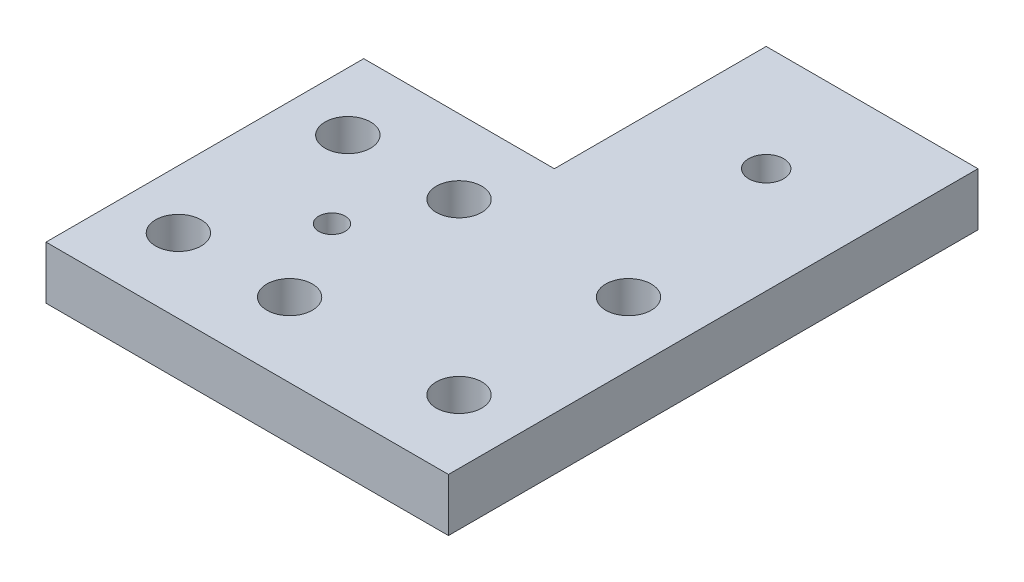
SolidWorks part; units mm, degrees
ref_plane "Ebene vorne" through (0, 0, 0) normal (0, 0, 1) x (1, 0, 0)
ref_plane "Ebene oben" through (0, 0, 0) normal (0, 1, 0) x (1, 0, 0)
ref_plane "Ebene rechts" through (0, 0, 0) normal (1, 0, 0) x (0, 0, -1)
sketch "Skizze1" plane through (0, 0, 0) normal (0, 1, 0) x (1, 0, 0)
  line L0 (-9, 15) -> (-9, -15)
  line L1 (-9, -15) -> (29, -15)
  line L2 (9, 35) -> (9, 15)
  line L3 (-9, 15) -> (9, 15)
  line L4 (29, -15) -> (29, 35)
  line L7 (9, 35) -> (29, 35)
  point P3 (0, 15)
  point P5 (-9, 0)
  dimension "D3" = 20
  dimension "D1" = 38
  dimension "D2" = 30
  dimension "D4" = 50
extrude "Aufsatz-Linear austragen1" add sketch "Skizze1" along normal blind 5 contours L0 L1 L4 L7 L2 L3
hole_wizard "Durchgangsloch für M41" positions "Skizze2" profile "Skizze3" hole size "M4" standard "DIN" end condition up to next
sketch "Skizze2" plane through (0, 5, 0) normal (0, 1, 0) x (1, 0, 0)
  line L1 (29, -15) -> (29, 35) construction
  line L2 (0, 0) -> (29, 0) construction
  line L3 (29, -15) -> (29, 35) construction
  point P0 (7, 8)
  point P2 (23, 8)
  point P4 (7, -8)
  point P6 (23, -8)
  dimension "D1" = 16
  dimension "D2" = 16
  dimension "D3" = 6
sketch "Skizze3" plane through (7, 5, -8) normal (1, 0, 0) x (0, 0, 1)
  line L0 (0, 0) -> (0, 5)
  line L1 (0, 5) -> (2.15, 5)
  line L2 (2.15, 5) -> (2.15, 0)
  line L5 (2.15, 0) -> (0, 0)
  line L11 (0, -6.35) -> (0, 107.95) construction
  dimension "Bohrerdurchmesser" = 4.3
  dimension "Bohrungstiefe" = 5
hole_wizard "Durchgangsloch für M42" positions "Skizze4" profile "Skizze5" hole size "M4" standard "DIN" end condition up to next
sketch "Skizze4" plane through (0, 5, 0) normal (0, 1, 0) x (1, 0, 0)
  line L2 (-9, 15) -> (-9, -15) construction
  line L3 (0, 0) -> (-9, 0) construction
  point P0 (-3.5, 8)
  point P2 (-3.5, -8)
  dimension "D1" = 16
  dimension "D3" = 5.5
sketch "Skizze5" plane through (-3.5, 5, -8) normal (1, 0, 0) x (0, 0, 1)
  line L0 (0, 0) -> (0, 5)
  line L1 (0, 5) -> (2.15, 5)
  line L2 (2.15, 5) -> (2.15, 0)
  line L5 (2.15, 0) -> (0, 0)
  line L11 (0, -6.35) -> (0, 107.95) construction
  dimension "Bohrerdurchmesser" = 4.3
  dimension "Bohrungstiefe" = 5
hole_wizard "M4 Gewindebohrung1" positions "Skizze6" profile "Skizze7" tap size "M4" standard "DIN" end condition through all
sketch "Skizze6" plane through (0, 5, 0) normal (0, 1, 0) x (1, 0, 0)
  line L0 (9, 35) -> (29, 35) construction
  point P0 (19, 25)
  point P6 (19, 35)
  dimension "D1" = 10
sketch "Skizze7" plane through (19, 5, -25) normal (1, 0, 0) x (0, 0, 1)
  line L0 (0, 0) -> (0, 5)
  line L1 (0, 5) -> (1.65, 5)
  line L2 (1.65, 5) -> (1.65, 0)
  line L5 (1.65, 0) -> (0, 0)
  line L11 (0, -6.35) -> (0, 107.95) construction
  dimension "Bohrerdurchmesser" = 3.3
  dimension "Bohrungstiefe" = 5
cosmetic thread "Bohrungsgewinde1" parameters "D2"=4
hole_wizard "M3 Gewindebohrung1" positions "Skizze8" profile "Skizze9" tap size "M3" standard "DIN" end condition up to next
sketch "Skizze8" plane through (0, 5, 0) normal (0, 1, 0) x (1, 0, 0)
  line L0 (-9, 0) -> (29, 0) construction
  line L1 (-9, 15) -> (-9, -15) construction
  line L2 (29, -15) -> (29, 35) construction
  point P0 (3, 0)
  dimension "D1" = 12
sketch "Skizze9" plane through (3, 5, 0) normal (1, 0, 0) x (0, 0, 1)
  line L0 (0, 0) -> (0, 5)
  line L1 (0, 5) -> (1.25, 5)
  line L2 (1.25, 5) -> (1.25, 0)
  line L5 (1.25, 0) -> (0, 0)
  line L11 (0, -6.35) -> (0, 107.95) construction
  dimension "Bohrerdurchmesser" = 2.5
  dimension "Bohrungstiefe" = 5
cosmetic thread "Bohrungsgewinde2" parameters "D2"=3
